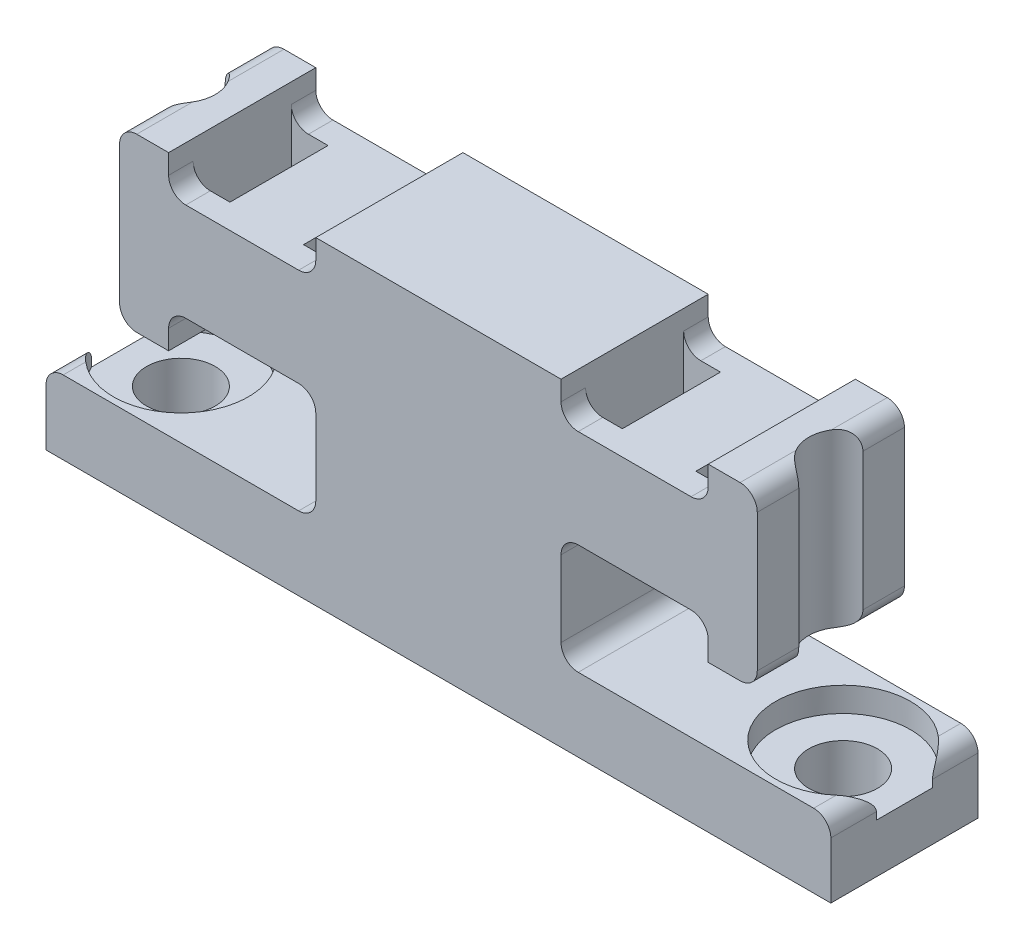
SolidWorks part; units mm, degrees
ref_plane "Front Plane" through (0, 0, 0) normal (0, 0, 1) x (1, 0, 0)
ref_plane "Top Plane" through (0, 0, 0) normal (0, 1, 0) x (1, 0, 0)
ref_plane "Right Plane" through (0, 0, 0) normal (1, 0, 0) x (0, 0, -1)
sketch "Sketch1" plane through (0, 0, 0) normal (0, 0, 1) x (1, 0, 0)
  line L0 (0, 0) -> (0, 13) construction
  line L1 (13, 13) -> (-13, 13)
  line L2 (-13, 13) -> (-13, 6)
  line L3 (-5, 3) -> (-16, 3)
  line L4 (-16, 3) -> (-16, 0)
  line L5 (-16, 0) -> (16, 0)
  line L6 (16, 3) -> (16, 0)
  line L7 (5, 3) -> (16, 3)
  line L8 (13, 13) -> (13, 6)
  line L9 (-13, 6) -> (-5, 6)
  line L18 (-5, 6) -> (-5, 3)
  line L19 (5, 3) -> (5, 6)
  line L20 (5, 6) -> (13, 6)
  point P2 (4.9584, 3)
  point P11 (-3.3288, 3)
  point P17 (2.1492, 3)
  dimension "D1" = 32
  dimension "D2" = 26
  dimension "D3" = 3
  dimension "D4" = 13
  dimension "D5" = 10
  dimension "D6" = 3
extrude "Boss-Extrude1" add sketch "Sketch1" along normal blind 6
sketch "Sketch4" plane through (0, 0, 6) normal (0, 0, 1) x (1, 0, 0)
  line L0 (-13, 6) -> (-5, 6) construction
  line L1 (-11, 6) -> (-5, 6)
  line L2 (-11, 6) -> (-11, 7.5)
  line L3 (-11, 7.5) -> (-5, 7.5)
  line L4 (-5, 6) -> (-5, 7.5)
  line L5 (13, 13) -> (-13, 13) construction
  line L6 (-11, 13) -> (-5, 13)
  line L7 (-11, 13) -> (-11, 11.5)
  line L8 (-11, 11.5) -> (-5, 11.5)
  line L9 (-5, 13) -> (-5, 11.5)
  line L19 (-5, 6) -> (-5, 3) construction
  line L20 (0, 0) -> (0, 13) construction
  line L21 (-13, 13) -> (-13, 6) construction
  line L22 (5, 13) -> (5, 11.5)
  line L23 (11, 11.5) -> (5, 11.5)
  line L24 (11, 13) -> (11, 11.5)
  line L25 (11, 13) -> (5, 13)
  line L26 (5, 6) -> (5, 7.5)
  line L27 (11, 7.5) -> (5, 7.5)
  line L28 (11, 6) -> (11, 7.5)
  line L29 (11, 6) -> (5, 6)
  dimension "D1" = 1.5
  dimension "D2" = 2
  dimension "D3" = 4
extrude "Cut-Extrude2" cut sketch "Sketch4" against normal through all
fillet "Fillet1" radius 0.7 16 edges at (5, 3, 3) (16, 3, 3) (-16, 3, 3) (-5, 7.5, 3) (-11, 7.5, 3) (-13, 6, 3) (-13, 13, 3) (-11, 11.5, 3) (-5, 11.5, 3) (5, 11.5, 3) (11, 11.5, 3) (13, 13, 3) (13, 6, 3) (11, 7.5, 3) (5, 7.5, 3) (-5, 3, 3)
sketch "Sketch2" plane through (0, 3, 0) normal (0, 1, 0) x (1, 0, 0)
  line L0 (-13.5, -3) -> (13.5, -3) construction
  line L1 (-16, -6) -> (-16, 0) construction
  circle A0 centre (-13.5, -3) radius 1.4
  circle A1 centre (13.5, -3) radius 1.4
  point P4 (-16, -3)
  point P7 (0, -3)
  dimension "D1" = 2.8
  dimension "D2" = 27
extrude "Cut-Extrude1" cut sketch "Sketch2" against normal through all both and the other way through all
sketch "Sketch5" plane through (0, 13, 0) normal (0, 1, 0) x (1, 0, 0)
  line L0 (-11, 0) -> (-11, -6) construction
  line L1 (-11, -1) -> (-9.5, -1)
  line L2 (-11, -1) -> (-11, -5)
  line L3 (-11, -5) -> (-9.5, -5)
  line L4 (-9.5, -1) -> (-9.5, -5)
  line L5 (-11, -6) -> (-11, 0) construction
  line L6 (-5, 0) -> (-5, -6) construction
  line L7 (-5, -1) -> (-6.5, -1)
  line L8 (-5, -1) -> (-5, -5)
  line L9 (-5, -5) -> (-6.5, -5)
  line L10 (-6.5, -1) -> (-6.5, -5)
  line L11 (-10.3, 0) -> (-11, 0) construction
  line L12 (0, 0) -> (0, -6) construction
  line L13 (5, 0) -> (-5, 0) construction
  line L14 (5, -6) -> (-5, -6) construction
  line L15 (5, -5) -> (6.5, -5)
  line L16 (6.5, -1) -> (6.5, -5)
  line L17 (5, -1) -> (6.5, -1)
  line L18 (5, -1) -> (5, -5)
  line L19 (11, -5) -> (9.5, -5)
  line L20 (9.5, -1) -> (9.5, -5)
  line L21 (11, -1) -> (9.5, -1)
  line L22 (11, -1) -> (11, -5)
  point P8 (-11, -3)
  point P9 (-11, -3)
  dimension "D1" = 1.5
  dimension "D2" = 1
  dimension "D3" = 4
extrude "Cut-Extrude3" cut sketch "Sketch5" against normal up to next
sketch "Sketch6" plane through (0, 3, 0) normal (0, 1, 0) x (1, 0, 0)
  circle A0 centre (13.5, -3) radius 2.75
  circle A1 centre (-13.5, -3) radius 2.75
  dimension "D1" = 5.5
extrude "Cut-Extrude5" cut sketch "Sketch6" against normal blind 1
